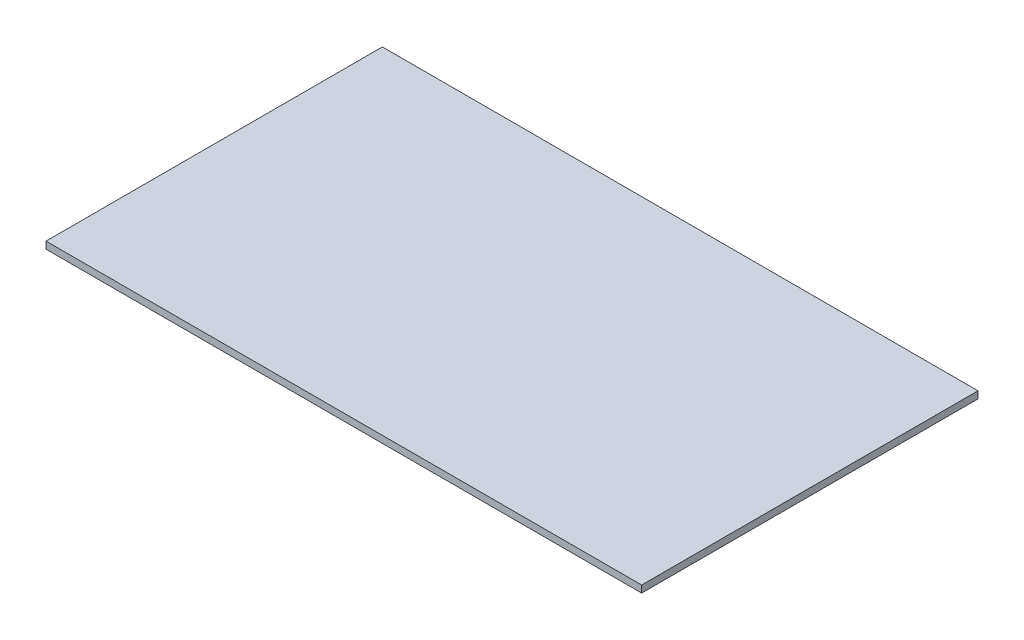
SolidWorks part; units mm, degrees
ref_plane "前视基准面" through (0, 0, 0) normal (0, 0, 1) x (1, 0, 0)
ref_plane "上视基准面" through (0, 0, 0) normal (0, 1, 0) x (1, 0, 0)
ref_plane "右视基准面" through (0, 0, 0) normal (1, 0, 0) x (0, 0, -1)
other "Configuration Table"
sketch "草图1" plane through (0, 0, 0) normal (0, 1, 0) x (1, 0, 0)
  line L1 (-42.5, -24) -> (42.5, -24)
  line L2 (-42.5, -24) -> (-42.5, 24)
  line L3 (-42.5, 24) -> (42.5, 24)
  line L4 (42.5, -24) -> (42.5, 24)
  line L5 (-42.5, -24) -> (42.5, 24) construction
  line L6 (-42.5, 24) -> (42.5, -24) construction
  point P0 (0, 0)
  dimension "D1" = 48
  dimension "D2" = 85
extrude "凸台-拉伸1" add sketch "草图1" along normal blind 1
